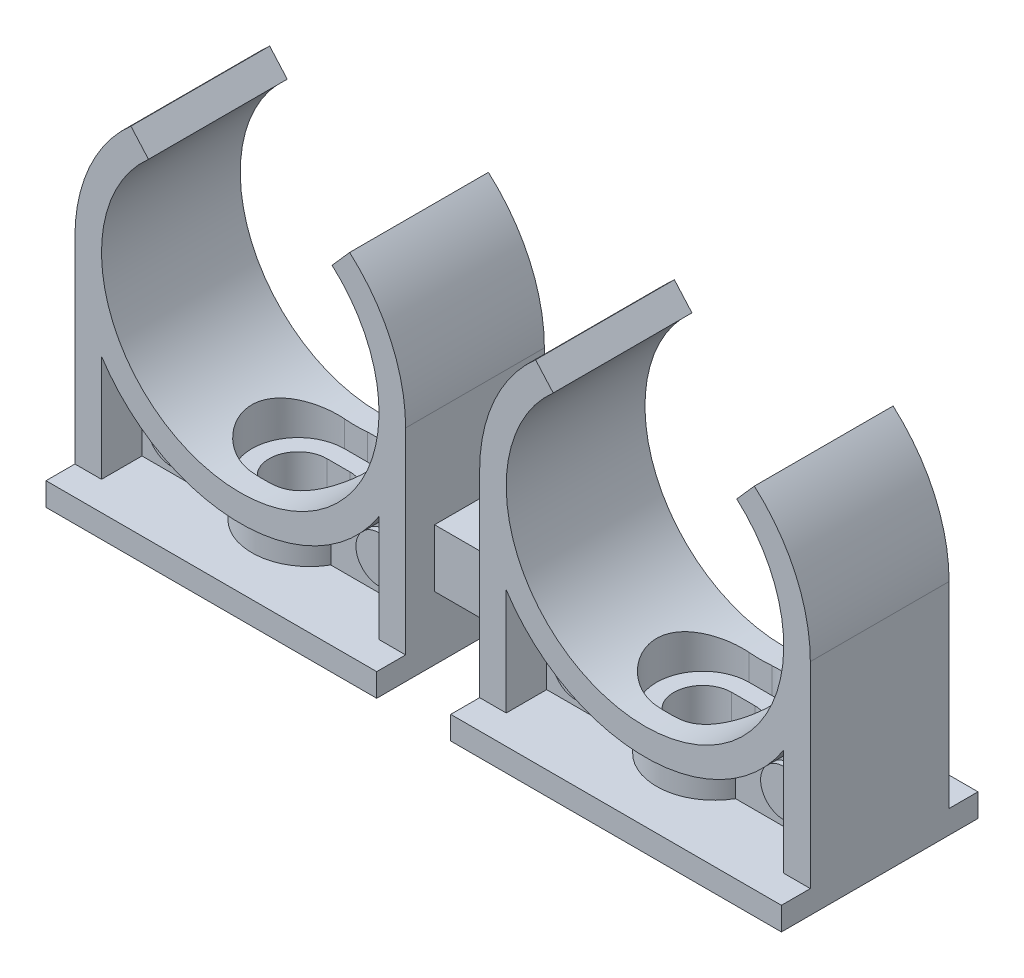
SolidWorks part; units mm, degrees
ref_plane "前视基准面" through (0, 0, 0) normal (0, 0, 1) x (1, 0, 0)
ref_plane "上视基准面" through (0, 0, 0) normal (0, 1, 0) x (1, 0, 0)
ref_plane "右视基准面" through (0, 0, 0) normal (1, 0, 0) x (0, 0, -1)
sketch "草图1" plane through (0, 0, 0) normal (0, 0, 1) x (1, 0, 0)
  line L0 (0, 30) -> (0, 0) construction
  line L1 (-17.5, 30) -> (-17.5, 0) construction
  line L2 (17.5, 30) -> (17.5, 0) construction
  line L3 (-31.5809, 7) -> (39.0457, 7)
  line L8 (-25.4373, 28) -> (-26.9586, 29.725)
  line L9 (-9.5627, 28) -> (-8.0414, 29.725)
  line L10 (9.5627, 28) -> (8.0414, 29.725)
  line L11 (25.4373, 28) -> (26.9586, 29.725)
  arc A0 (-25.4373, 28) -> (-9.5627, 28) centre (-17.5, 19) ccw
  arc A1 (9.5627, 28) -> (25.4373, 28) centre (17.5, 19) ccw
  arc A2 (-26.9586, 29.725) -> (-8.0414, 29.725) centre (-17.5, 19) ccw
  arc A3 (8.0414, 29.725) -> (26.9586, 29.725) centre (17.5, 19) ccw
  dimension "D8" = 24
  dimension "D9" = 24
  dimension "D10" = 2.3
  dimension "D11" = 2.3
  dimension "D1" = 30
  dimension "D2" = 35
  dimension "D3" = 17.5
  dimension "D4" = 7
  dimension "D5" = 12
  dimension "D6" = 12
extrude "凸台-拉伸1" add sketch "草图1" along normal blind 12 contours A0 L9 A2 L8 | A1 L11 A3 L10
ref_plane "基准面4" through (0, 0, 14.5) normal (0, 0, 1) x (1, 0, 0)
ref_plane "基准面5" through (0, 0, -2.5) normal (0, 0, -1) x (-1, 0, 0)
sketch "草图2" plane through (0, 0, 14.5) normal (0, 0, 1) x (1, 0, 0)
  line L0 (-31.8, 2) -> (-31.8, 0)
  line L1 (-31.8, 0) -> (-3.2, 0)
  line L2 (-3.2, 0) -> (-3.2, 2)
  line L3 (0, -6.7744) -> (0, 41.3145) construction
  line L4 (3.2, 0) -> (3.2, 2)
  line L5 (31.8, 2) -> (3.2, 2)
  line L6 (31.8, 0) -> (31.8, 2)
  line L7 (31.8, 0) -> (3.2, 0)
  line L8 (3.2, 0) -> (3.2, 2)
  line L9 (-31.8, 0) -> (-3.2, 0)
  line L10 (-31.8, 0) -> (-31.8, 2)
  line L11 (-31.8, 2) -> (-3.2, 2)
  line L12 (-3.2, 0) -> (-3.2, 2)
  line L13 (31.8, 0) -> (3.2, 0)
  line L14 (31.8, 2) -> (31.8, 0)
  arc A0 (-26.9586, 29.725) -> (-8.0414, 29.725) centre (-17.5, 19) ccw construction
  arc A2 (-31.8, 19) -> (-29.5, 11.2225) centre (-17.5, 19) ccw
  arc A3 (-31.8, 19) -> (-29.5, 11.2225) centre (-17.5, 19) ccw
  arc A4 (-31.8, 19) -> (-29.5, 11.2225) centre (-17.5, 19) ccw
  dimension "D1" = 2
extrude "凸台-拉伸2" add sketch "草图2" against normal blind 17 separate body contours L11 L0 L1 L2 | L7 L6 L5 L4
sketch "草图3" plane through (0, 0, 12) normal (0, 0, 1) x (1, 0, 0)
  line L0 (-31.8, 2) -> (-3.2, 2) construction
  line L1 (-31.8, 19) -> (-29.5, 19)
  line L2 (-31.8, 19) -> (-31.8, 2)
  line L3 (-31.8, 2) -> (-29.5, 2)
  line L4 (-29.5, 19) -> (-29.5, 2)
  line L5 (-17.5, -4.6048) -> (-17.5, 43.5605) construction
  line L6 (0, -5.2822) -> (0, 46.7214) construction
  line L7 (17.5, -4.1533) -> (17.5, 42.8832) construction
  line L8 (-3.2, 2) -> (-5.5, 2)
  line L9 (-5.5, 19) -> (-5.5, 2)
  line L10 (-3.2, 19) -> (-5.5, 19)
  line L11 (-3.2, 19) -> (-3.2, 2)
  line L12 (5.5, 19) -> (5.5, 2)
  line L13 (31.8, 2) -> (29.5, 2)
  line L14 (29.5, 19) -> (29.5, 2)
  line L15 (31.8, 19) -> (29.5, 19)
  line L16 (31.8, 19) -> (31.8, 2)
  line L17 (5.5, 19) -> (5.5, 2)
  line L18 (3.2, 19) -> (5.5, 19)
  line L19 (3.2, 19) -> (3.2, 2)
  line L20 (3.2, 2) -> (5.5, 2)
  arc A0 (-26.9586, 29.725) -> (-8.0414, 29.725) centre (-17.5, 19) ccw construction
  arc A1 (-25.4373, 28) -> (-9.5627, 28) centre (-17.5, 19) ccw construction
  arc M10 (-26.9586, 29.725) -> (-8.0414, 29.725) centre (-17.5, 19) ccw
extrude "凸台-拉伸3" add sketch "草图3" against normal blind 12 contours L4 L2 L3 M10 | L11 L9 L8 M10 | L19 L20 L12 L18 | L16 L15 L14 L13
ref_plane "基准面6" through (0, 0, 6) normal (0, 0, 1) x (1, 0, 0)
sketch "草图4" plane through (0, 0, 6) normal (0, 0, 1) x (1, 0, 0)
  line L0 (-29.5, 2) -> (-5.5, 2)
  line L1 (-5.5, 2) -> (-5.5, 11.2225)
  line L2 (-5.5, 11.2225) -> (-8.3616, 11.2225)
  line L3 (-29.5, 11.2225) -> (-29.5, 2)
  line L4 (-26.6384, 11.2225) -> (-29.5, 11.2225)
  line L5 (0, 0) -> (0, 41.7333) construction
  line L6 (26.6384, 11.2225) -> (29.5, 11.2225)
  line L7 (29.5, 11.2225) -> (29.5, 2)
  line L8 (29.5, 2) -> (5.5, 2)
  line L9 (5.5, 2) -> (5.5, 11.2225)
  line L10 (5.5, 11.2225) -> (8.3616, 11.2225)
  arc A0 (-26.6384, 11.2225) -> (-8.3616, 11.2225) centre (-17.5, 19) ccw
  arc A1 (26.6384, 11.2225) -> (8.3616, 11.2225) centre (17.5, 19) cw
extrude "凸台-拉伸4" add sketch "草图4" along normal mid plane 5
sketch "草图5" plane through (0, 0, 6) normal (0, 0, 1) x (1, 0, 0)
  line L0 (-17.5, 0) -> (-17.5, 35.8396) construction
  line L1 (-31.8, 0) -> (-3.2, 0) construction
  line L2 (0, 0) -> (0, 38.8128) construction
  line L3 (17.5, 0) -> (17.5, 35.8396) construction
  line L4 (-29.5, 2) -> (-5.5, 2) construction
  line L5 (-29.5, 11.2225) -> (-29.5, 2) construction
  circle A0 centre (-26.5, 5) radius 2
  circle A1 centre (-8.5, 5) radius 2
  circle A2 centre (8.5, 5) radius 2
  circle A3 centre (26.5, 5) radius 2
  dimension "D1" = 4
  dimension "D2" = 3
  dimension "D3" = 3
extrude "凸台-拉伸5" add sketch "草图5" along normal mid plane 6
sketch "草图6" plane through (0, 0, 0) normal (0, 1, 0) x (1, 0, 0)
  line L0 (-39.2454, -6) -> (37.5936, -6)
  line L1 (-17.5, 2.5) -> (-17.5, -14.5)
  line L2 (-31.8, 2.5) -> (-3.2, 2.5) construction
  line L3 (-31.8, -14.5) -> (-3.2, -14.5) construction
  line L4 (17.5, -14.5) -> (17.5, 2.5)
  line L5 (31.8, -14.5) -> (3.2, -14.5) construction
  line L6 (31.8, 2.5) -> (3.2, 2.5) construction
sketch "草图9" plane through (0, 0, 12) normal (0, 0, 1) x (1, 0, 0)
  arc A0 (-25.4373, 28) -> (-9.5627, 28) centre (-17.5, 19) ccw construction
  point P0 (-17.5, 7)
ref_plane "基准面7" through (0, 7, 0) normal (0, -1, 0) x (-1, 0, 0)
sketch "草图10" plane through (0, 7, 0) normal (0, -1, 0) x (-1, 0, 0)
  line L0 (31.8, -6) -> (-31.8, -6) construction
  line L1 (31.8, 0) -> (31.8, -12) construction
  line L2 (-31.8, 0) -> (-31.8, -12) construction
  line L3 (17.5, 2.5) -> (17.5, -2) construction
  line L4 (31.8, 2.5) -> (3.2, 2.5) construction
  line L5 (31.8, -14.5) -> (3.2, -14.5) construction
  line L6 (-17.5, 2.5) -> (-17.5, -2) construction
  line L7 (-31.8, 2.5) -> (-3.2, 2.5) construction
  line L8 (-31.8, -14.5) -> (-3.2, -14.5) construction
  line L10 (18.5, -2) -> (16.5, -2)
  line L12 (18.5, -10) -> (16.5, -10)
  line L14 (-16.5, -2) -> (-18.5, -2)
  line L16 (-16.5, -10) -> (-18.5, -10)
  line L18 (17.5, -10) -> (17.5, -14.5) construction
  line L21 (-17.5, -10) -> (-17.5, -14.5) construction
  arc A0 (18.5, -10) -> (18.5, -2) centre (18.5, -6) ccw
  arc A1 (16.5, -2) -> (16.5, -10) centre (16.5, -6) ccw
  arc A2 (-16.5, -10) -> (-16.5, -2) centre (-16.5, -6) ccw
  arc A3 (-18.5, -2) -> (-18.5, -10) centre (-18.5, -6) ccw
  dimension "D1" = 8
  dimension "D2" = 2
  dimension "D3" = 4
  dimension "D5" = 8
  dimension "D8" = 4
extrude "切除-拉伸4" cut sketch "草图10" along normal mid plane 2.5
sketch "草图11" plane through (0, 5.75, 0) normal (0, 1, 0) x (1, 0, 0)
  line L4 (-18.5, -3.5) -> (-16.5, -3.5)
  line L5 (-16.5, -8.5) -> (-18.5, -8.5)
  line L6 (0, 0) -> (0, -18.0498) construction
  line L7 (16.5, -8.5) -> (18.5, -8.5)
  line L8 (18.5, -3.5) -> (16.5, -3.5)
  arc A4 (-18.5, -8.5) -> (-18.5, -3.5) centre (-18.5, -6) cw
  arc A5 (-16.5, -3.5) -> (-16.5, -8.5) centre (-16.5, -6) cw
  arc A6 (18.5, -8.5) -> (18.5, -3.5) centre (18.5, -6) ccw
  arc A7 (16.5, -3.5) -> (16.5, -8.5) centre (16.5, -6) ccw
extrude "切除-拉伸5" cut sketch "草图11" against normal through all
sketch "草图12" plane through (0, 2, 0) normal (0, 1, 0) x (1, 0, 0)
  line L0 (0, 0) -> (0, -20.238) construction
  circle A0 centre (-17.5, -6) radius 4
  circle A1 centre (-17.5, -6) radius 5
  circle A2 centre (17.5, -6) radius 5
  circle A3 centre (17.5, -6) radius 4
extrude "凸台-拉伸9" add sketch "草图12" along normal up to next
sketch "草图13" plane through (0, 2, 0) normal (0, 1, 0) x (1, 0, 0)
  line L0 (-18.5, -3.5) -> (-16.5, -3.5)
  line L1 (-16.5, -8.5) -> (-18.5, -8.5)
  line L2 (-16.5, -10) -> (-18.5, -10)
  line L3 (-18.5, -2) -> (-16.5, -2)
  line L4 (0, 0) -> (0, -15.3863) construction
  line L5 (18.5, -2) -> (16.5, -2)
  line L6 (16.5, -10) -> (18.5, -10)
  line L7 (16.5, -8.5) -> (18.5, -8.5)
  line L8 (18.5, -3.5) -> (16.5, -3.5)
  arc A0 (-16.5, -8.5) -> (-16.5, -3.5) centre (-16.5, -6) ccw
  arc A1 (-18.5, -3.5) -> (-18.5, -8.5) centre (-18.5, -6) ccw
  arc A2 (-18.5, -2) -> (-18.5, -10) centre (-18.5, -6) ccw
  arc A3 (-16.5, -10) -> (-16.5, -2) centre (-16.5, -6) ccw
  arc A4 (16.5, -10) -> (16.5, -2) centre (16.5, -6) cw
  arc A5 (18.5, -2) -> (18.5, -10) centre (18.5, -6) cw
  arc A6 (18.5, -3.5) -> (18.5, -8.5) centre (18.5, -6) cw
  arc A7 (16.5, -8.5) -> (16.5, -3.5) centre (16.5, -6) cw
  dimension "D1" = 1.5
extrude "凸台-拉伸10" add sketch "草图13" along normal blind 4.8
sketch "草图14" plane through (0, 6.8, 0) normal (0, 1, 0) x (1, 0, 0)
  line L0 (-18.5, -2) -> (-16.5, -2)
  line L1 (-18.5, -10) -> (-16.5, -10)
  line L2 (0, 0) -> (0, -11.8849) construction
  line L3 (18.5, -10) -> (16.5, -10)
  line L4 (18.5, -2) -> (16.5, -2)
  arc A0 (-18.5, -2) -> (-18.5, -10) centre (-18.5, -6) ccw
  arc A2 (-16.5, -10) -> (-16.5, -2) centre (-16.5, -6) ccw
  arc A3 (18.5, -2) -> (18.5, -10) centre (18.5, -6) cw
  arc A4 (16.5, -10) -> (16.5, -2) centre (16.5, -6) cw
extrude "切除-拉伸6" cut sketch "草图14" against normal blind 2
sketch "草图15" plane through (0, 0, 12) normal (0, 0, 1) x (1, 0, 0)
  line L0 (-3.2, 19) -> (-3.2, 2) construction
  line L1 (-3.2, 10.5) -> (3.2, 10.5)
  line L2 (-3.2, 10.5) -> (-3.2, 5.5)
  line L3 (-3.2, 5.5) -> (3.2, 5.5)
  line L4 (3.2, 10.5) -> (3.2, 5.5)
  line L5 (3.2, 19) -> (3.2, 2) construction
  dimension "D1" = 5
extrude "凸台-拉伸11" add sketch "草图15" against normal up to surface (12 mm away) up to face at (-17.5, 13.1179, 0)
sketch "草图16" plane through (0, 0, 12) normal (0, 0, 1) x (1, 0, 0)
  line L1 (-3.2, 10.5) -> (3.2, 10.5)
  line L2 (-3.2, 10.5) -> (-3.2, 5.5)
  line L3 (-3.2, 5.5) -> (3.2, 5.5)
  line L4 (3.2, 10.5) -> (3.2, 5.5)
extrude "切除-拉伸7" cut sketch "草图16" against normal blind 2.5
sketch "草图17" plane through (0, 0, 0) normal (0, 0, -1) x (-1, 0, 0)
  line L0 (-3.2, 10.5) -> (3.2, 10.5)
  line L1 (3.2, 10.5) -> (3.2, 5.5)
  line L2 (3.2, 5.5) -> (-3.2, 5.5)
  line L3 (-3.2, 5.5) -> (-3.2, 10.5)
extrude "切除-拉伸8" cut sketch "草图17" against normal blind 2.5
